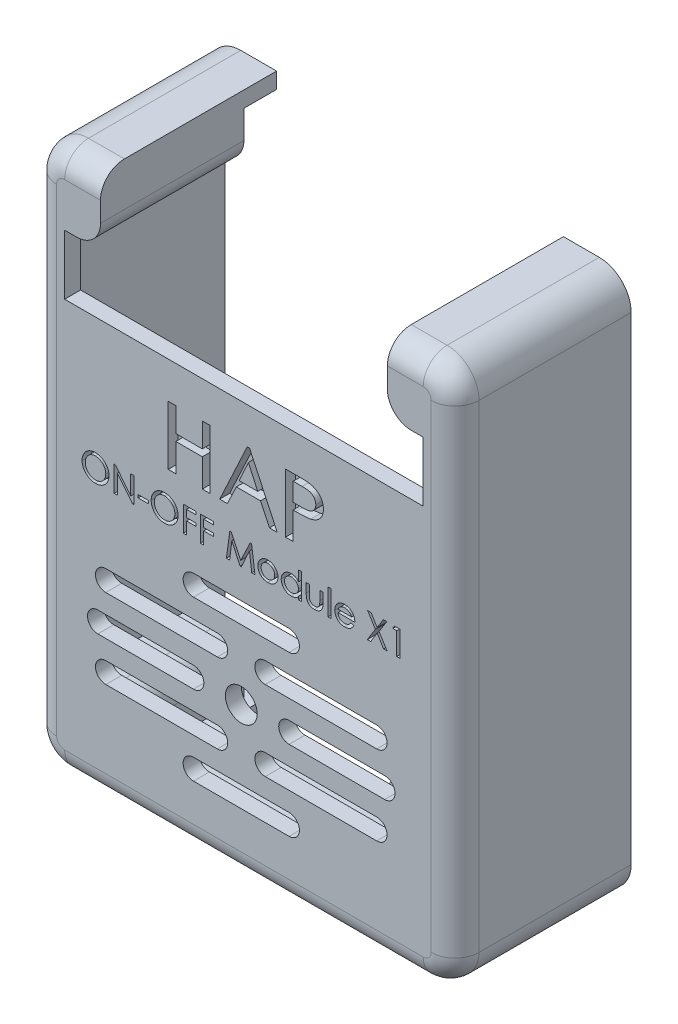
SolidWorks part; units mm, degrees
material "ABS"
ref_plane "Plano frontal" through (0, 0, 0) normal (0, 0, 1) x (1, 0, 0)
ref_plane "Plano superior" through (0, 0, 0) normal (0, 1, 0) x (1, 0, 0)
ref_plane "Plano direito" through (0, 0, 0) normal (1, 0, 0) x (0, 0, -1)
sketch "Esboço1" plane through (0, 0, 0) normal (0, 0, 1) x (1, 0, 0)
  line L1 (-26.5, -34) -> (26.5, -34)
  line L2 (-26.5, -34) -> (-26.5, 34)
  line L3 (-26.5, 34) -> (26.5, 34)
  line L4 (26.5, -34) -> (26.5, 34)
  point P0 (0, 0)
  point P6 (0, 34)
  point P7 (26.5, 0)
  dimension "D1" = 53
  dimension "D2" = 68
  dimension "D3" = 0
  dimension "D4" = 0
extrude "Ressalto-extrusão1" add sketch "Esboço1" along normal blind 22.1
fillet "Filete1" radius 4 4 edges at (-26.5, -34, 11.05) (26.5, -34, 11.05) (-26.5, 34, 11.05) (26.5, 34, 11.05)
fillet "Filete2" radius 3 8 edges at (0, 34, 22.1) (26.5, 0, 22.1) (25.3284, -32.8284, 22.1) (0, -34, 22.1) (-25.3284, -32.8284, 22.1) (-26.5, 0, 22.1) (-25.3284, 32.8284, 22.1) (25.3284, 32.8284, 22.1)
shell "Casca1" thickness 2
sketch "Esboço3" plane through (0, 0, 20.1) normal (0, 0, -1) x (-1, 0, 0)
  line L0 (0, 0) -> (0, -34) construction
  line L1 (22.5, -34) -> (-22.5, -34) construction
  line L2 (0, 0) -> (26.5, 0) construction
  line L3 (26.5, 30) -> (26.5, -30) construction
  line L4 (-18, -28.5) -> (-18, -32)
  line L5 (-22.5, -32) -> (22.5, -32) construction
  line L6 (-21, -25.5) -> (-24.5, -25.5)
  line L7 (-24.5, 30) -> (-24.5, -30) construction
  line L8 (-24.5, -30) -> (-24.5, -25.5)
  line L9 (-22.5, -32) -> (-18, -32)
  line L10 (22.5, -32) -> (18, -32)
  line L11 (24.5, -30) -> (24.5, -25.5)
  line L12 (21, -25.5) -> (24.5, -25.5)
  line L13 (18, -28.5) -> (18, -32)
  line L14 (18, 28.5) -> (18, 32)
  line L15 (21, 25.5) -> (24.5, 25.5)
  line L16 (24.5, 30) -> (24.5, 25.5)
  line L17 (22.5, 32) -> (18, 32)
  line L18 (-22.5, 32) -> (-18, 32)
  line L19 (-24.5, 30) -> (-24.5, 25.5)
  line L20 (-21, 25.5) -> (-24.5, 25.5)
  line L21 (-18, 28.5) -> (-18, 32)
  arc A0 (-18, -28.5) -> (-21, -25.5) centre (-21, -28.5) ccw
  arc A4 (-24.5, -30) -> (-22.5, -32) centre (-22.5, -30) ccw
  arc A5 (24.5, -30) -> (22.5, -32) centre (22.5, -30) cw
  arc A6 (18, -28.5) -> (21, -25.5) centre (21, -28.5) cw
  arc A7 (18, 28.5) -> (21, 25.5) centre (21, 28.5) ccw
  arc A8 (24.5, 30) -> (22.5, 32) centre (22.5, 30) ccw
  arc A9 (-24.5, 30) -> (-22.5, 32) centre (-22.5, 30) cw
  arc A10 (-18, 28.5) -> (-21, 25.5) centre (-21, 28.5) cw
  dimension "D1" = 21
  dimension "D2" = 28.5
  dimension "D3" = 6
extrude "Ressalto-extrusão2" add sketch "Esboço3" along normal blind 16
sketch "Esboço4" plane through (0, 0, 4.1) normal (0, 0, -1) x (-1, 0, 0)
  line L0 (0, -34) -> (0, 34) construction
  line L1 (22.5, -34) -> (-22.5, -34) construction
  line L2 (-22.5, 34) -> (22.5, 34) construction
  line L3 (-26.5, 0) -> (26.5, 0) construction
  line L4 (-26.5, -30) -> (-26.5, 30) construction
  line L5 (26.5, 30) -> (26.5, -30) construction
  circle A0 centre (-21, -28.5) radius 1
  circle A2 centre (21, -28.5) radius 1
  circle A3 centre (-21, 28.5) radius 1
  circle A4 centre (21, 28.5) radius 1
  dimension "D1" = 2
extrude "Corte-extrusão1" cut sketch "Esboço4" against normal blind 6
sketch "Esboço5" plane through (0, 0, 22.1) normal (0, 0, 1) x (1, 0, 0)
  line L0 (-22.5, 34) -> (22.5, 34) construction
  line L1 (-18, 34) -> (18, 34)
  line L2 (-18, 34) -> (-18, 28.5)
  line L3 (-22.5, 18) -> (22.5, 18)
  line L4 (18, 34) -> (18, 28.5)
  line L5 (21, 25.5) -> (22.5, 25.5)
  line L8 (22.5, 25.5) -> (22.5, 18)
  line L9 (0, 34) -> (0, 0) construction
  line L10 (-22.5, 25.5) -> (-22.5, 18)
  line L11 (-21, 25.5) -> (-22.5, 25.5)
  arc A0 (18, 28.5) -> (21, 25.5) centre (21, 28.5) ccw
  arc A1 (-18, 28.5) -> (-21, 25.5) centre (-21, 28.5) cw
  dimension "D1" = 18
  dimension "D2" = 18
  dimension "D4" = 22.5
extrude "Corte-extrusão2" cut sketch "Esboço5" against normal through all
sketch "Esboço6" plane through (0, 0, 0) normal (0, 0, -1) x (-1, 0, 0)
  line L5 (-18, -32) -> (18, -32) construction
  line L6 (-0.5, -32) -> (16.5, -32)
  line L7 (-0.5, -32) -> (-0.5, -34)
  line L8 (-0.5, -34) -> (16.5, -34)
  line L9 (16.5, -32) -> (16.5, -34)
  line L10 (22.5, -34) -> (-22.5, -34) construction
  line L11 (26.5, 30) -> (26.5, -30) construction
  dimension "D1" = 10
  dimension "D2" = 17
extrude "Corte-extrusão3" cut sketch "Esboço6" against normal blind 6
sketch "Esboço7" plane through (0, -34, 0) normal (0, -1, 0) x (1, 0, 0)
  line L0 (-16.5, 0) -> (-18.5, 0)
  line L1 (-22.5, 0) -> (-16.5, 0) construction
  line L2 (-18.5, 0) -> (-18.5, 8)
  line L3 (-18.5, 8) -> (2.5, 8)
  line L4 (2.5, 8) -> (2.5, 0)
  line L5 (0.5, 0) -> (22.5, 0) construction
  line L6 (2.5, 0) -> (0.5, 0)
  line L7 (0.5, 0) -> (0.5, 6)
  line L8 (0.5, 6) -> (-16.5, 6)
  line L9 (-16.5, 6) -> (-16.5, 0)
  dimension "D1" = 2
  dimension "D2" = 2
  dimension "D3" = 2
extrude "Ressalto-extrusão3" add sketch "Esboço7" along normal blind 4.5
sketch "Esboço8" plane through (0, -38.5, 0) normal (0, -1, 0) x (1, 0, 0)
  line L1 (-18.5, 0) -> (2.5, 0)
  line L2 (-18.5, 0) -> (-18.5, 8)
  line L3 (-18.5, 8) -> (2.5, 8)
  line L4 (2.5, 0) -> (2.5, 8)
extrude "Ressalto-extrusão4" add sketch "Esboço8" along normal blind 1.5
fillet "Filete3" radius 1 8 edges at (-18.5, -37, 8) (-8, -40, 8) (2.5, -37, 8) (2.5, -34, 4) (-18.5, -34, 4) (-8, -34, 8) (2.5, -40, 4) (-18.5, -40, 4)
sketch "Esboço10" plane through (0, 0, 22.1) normal (0, 0, 1) x (1, 0, 0)
  line L0 (-23.5, 6) -> (23.5, 6) construction
  line L1 (-23.5, 30) -> (-23.5, -30) construction
  line L2 (23.5, -30) -> (23.5, 30) construction
  line L3 (-22.5, 18) -> (22.5, 18) construction
  line L4 (-23.5, 0) -> (23.5, 0) construction
  dimension "D1" = 12
  dimension "D2" = 6
sketch "Esboço11" plane through (0, 0, 22.1) normal (0, 0, 1) x (1, 0, 0)
  text T0 "HAP" font "Century Gothic" height in points 28
  text T1 "ON-OFF Module X1" font "Century Gothic" height in points 12
extrude "Corte-extrusão5" cut sketch "Esboço11" against normal blind 1.25
sketch "Esboço15" plane through (0, 0, 22.1) normal (0, 0, 1) x (1, 0, 0)
  line L0 (-18.3326, -13.6963) -> (-6.3326, -13.6963)
  line L1 (-18.3326, -16.2963) -> (-6.3326, -16.2963)
  line L2 (-0.3326, -12.9963) -> (-0.3326, -16.9963) construction
  line L3 (17.6674, -16.2963) -> (5.6674, -16.2963)
  line L4 (17.6674, -13.6963) -> (5.6674, -13.6963)
  circle A0 centre (-0.3326, -14.9963) radius 2
  arc A1 (-6.3326, -16.2963) -> (-6.3326, -13.6963) centre (-6.3326, -14.9963) ccw
  arc A2 (-18.3326, -13.6963) -> (-18.3326, -16.2963) centre (-18.3326, -14.9963) ccw
  arc A3 (17.6674, -13.6963) -> (17.6674, -16.2963) centre (17.6674, -14.9963) cw
  arc A4 (5.6674, -16.2963) -> (5.6674, -13.6963) centre (5.6674, -14.9963) cw
  dimension "D1" = 15
  dimension "D2" = 4
  dimension "D3" = 2.6
  dimension "D4" = 2.6
  dimension "D5" = 6
  dimension "D6" = 0
  dimension "D8" = 0
  dimension "D7" = 12
extrude "Corte-extrusão6" cut sketch "Esboço15" against normal through all
sketch "Esboço16" plane through (0, 0, 22.1) normal (0, 0, 1) x (1, 0, 0)
  line L0 (-19.6326, -14.9963) -> (18.9674, -14.9963) construction
  line L1 (-0.3326, -12.9963) -> (-0.3326, -16.9963) construction
  line L2 (-17.3326, -8.6963) -> (-3.3326, -8.6963)
  line L3 (-17.3326, -11.2963) -> (-3.3326, -11.2963)
  line L4 (16.6674, -11.2963) -> (2.6674, -11.2963)
  line L5 (16.6674, -8.6963) -> (2.6674, -8.6963)
  line L6 (16.6674, -21.2963) -> (2.6674, -21.2963)
  line L7 (16.6674, -18.6963) -> (2.6674, -18.6963)
  line L8 (-17.3326, -18.6963) -> (-3.3326, -18.6963)
  line L9 (-17.3326, -21.2963) -> (-3.3326, -21.2963)
  arc A0 (-18.3326, -13.6963) -> (-18.3326, -16.2963) centre (-18.3326, -14.9963) ccw construction
  arc A1 (17.6674, -16.2963) -> (17.6674, -13.6963) centre (17.6674, -14.9963) ccw construction
  arc A2 (-17.3326, -8.6963) -> (-17.3326, -11.2963) centre (-17.3326, -9.9963) ccw
  arc A3 (-3.3326, -11.2963) -> (-3.3326, -8.6963) centre (-3.3326, -9.9963) ccw
  circle A4 centre (-0.3326, -14.9963) radius 2 construction
  arc A5 (2.6674, -11.2963) -> (2.6674, -8.6963) centre (2.6674, -9.9963) cw
  arc A6 (16.6674, -8.6963) -> (16.6674, -11.2963) centre (16.6674, -9.9963) cw
  arc A7 (16.6674, -21.2963) -> (16.6674, -18.6963) centre (16.6674, -19.9963) ccw
  arc A8 (2.6674, -18.6963) -> (2.6674, -21.2963) centre (2.6674, -19.9963) ccw
  arc A9 (-3.3326, -18.6963) -> (-3.3326, -21.2963) centre (-3.3326, -19.9963) cw
  arc A10 (-17.3326, -21.2963) -> (-17.3326, -18.6963) centre (-17.3326, -19.9963) cw
  dimension "D1" = 2.6
  dimension "D2" = 2.6
  dimension "D3" = 14
  dimension "D4" = 3
  dimension "D5" = 5
extrude "Corte-extrusão7" cut sketch "Esboço16" against normal through all
sketch "Esboço17" plane through (0, 0, 22.1) normal (0, 0, 1) x (1, 0, 0)
  line L0 (-2.3326, -14.9963) -> (1.6674, -14.9963) construction
  line L1 (-6.3326, -6.2963) -> (5.6674, -6.2963)
  line L2 (-6.3326, -3.6963) -> (5.6674, -3.6963)
  line L3 (-6.3326, -26.2963) -> (5.6674, -26.2963)
  line L4 (-6.3326, -23.6963) -> (5.6674, -23.6963)
  circle A0 centre (-0.3326, -14.9963) radius 2 construction
  arc A1 (-6.3326, -3.6963) -> (-6.3326, -6.2963) centre (-6.3326, -4.9963) ccw
  arc A2 (5.6674, -6.2963) -> (5.6674, -3.6963) centre (5.6674, -4.9963) ccw
  arc A3 (-3.3326, -11.2963) -> (-3.3326, -8.6963) centre (-3.3326, -9.9963) ccw construction
  arc A4 (5.6674, -23.6963) -> (5.6674, -26.2963) centre (5.6674, -24.9963) cw
  arc A5 (-6.3326, -26.2963) -> (-6.3326, -23.6963) centre (-6.3326, -24.9963) cw
  dimension "D1" = 5
  dimension "D2" = 2.6
  dimension "D3" = 2.6
  dimension "D4" = 0
  dimension "D5" = 6
  dimension "D6" = 6
extrude "Corte-extrusão8" cut sketch "Esboço17" against normal through all
